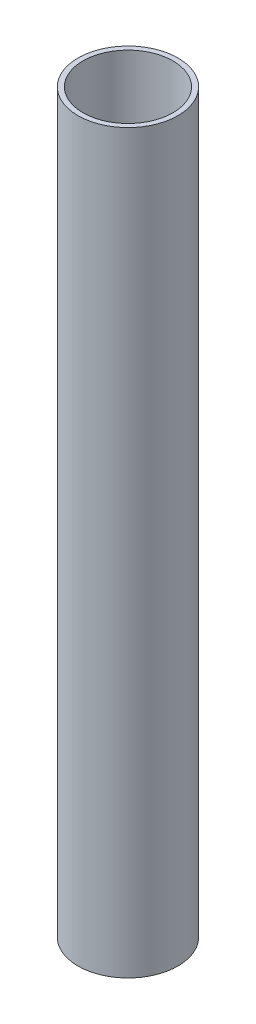
SolidWorks part; units mm, degrees
material "Thornel Mat VMA"
ref_plane "Front Plane" through (0, 0, 0) normal (0, 0, 1) x (1, 0, 0)
ref_plane "Top Plane" through (0, 0, 0) normal (0, 1, 0) x (1, 0, 0)
ref_plane "Right Plane" through (0, 0, 0) normal (1, 0, 0) x (0, 0, -1)
sketch "Sketch1" plane through (0, 0, 0) normal (0, 1, 0) x (1, 0, 0)
  circle A0 centre (0, 0) radius 13.5
  circle A1 centre (0, 0) radius 15
  dimension "D1" = 30
  dimension "D2" = 27
extrude "Boss-Extrude1" add sketch "Sketch1" along normal blind 221
